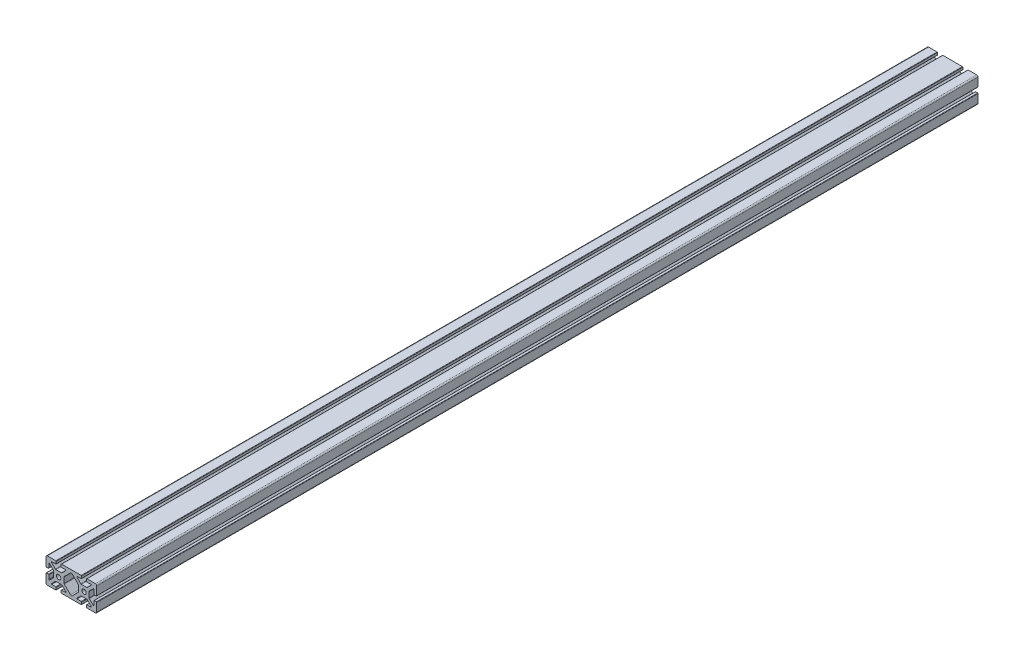
SolidWorks part; units mm, degrees
material "1060 Alloy"
ref_plane "Front Plane" through (0, 0, 0) normal (0, 0, 1) x (1, 0, 0)
ref_plane "Top Plane" through (0, 0, 0) normal (0, 1, 0) x (1, 0, 0)
ref_plane "Right Plane" through (0, 0, 0) normal (1, 0, 0) x (0, 0, -1)
sketch "Sketch1" plane through (0, 0, 0) normal (0, 0, 1) x (1, 0, 0)
  line L6 (11.2056, -5.1821) -> (1.4849, -14.9028)
  line L7 (-11.2056, -5.1821) -> (-1.4849, -14.9028)
  line L8 (-11.5571, 4.3336) -> (-11.5571, -4.3336)
  line L9 (-11.2056, 5.1821) -> (-1.4849, 14.9028)
  line L10 (11.2056, 5.1821) -> (1.4849, 14.9028)
  line L11 (11.5571, 4.3336) -> (11.5571, -4.3336)
  line L122 (-30.9, 15.5179) -> (-24.6, 15.5179)
  line L123 (-24, 16.1179) -> (-24, 19.4)
  line L124 (-24.6, 20) -> (-37.9, 20)
  line L125 (-40, 17.9) -> (-40, 4.6)
  line L126 (-39.4, 4) -> (-36.1179, 4)
  line L127 (-35.5179, 4.6) -> (-35.5179, 10.9)
  line L128 (-34.4936, 11.3243) -> (-28.3515, 5.1821)
  line L129 (-28, 4.3336) -> (-28, -4.3336)
  line L130 (-28.3515, -5.1821) -> (-34.4936, -11.3243)
  line L131 (-35.5179, -10.9) -> (-35.5179, -4.6)
  line L132 (-36.1179, -4) -> (-39.4, -4)
  line L133 (-40, -4.6) -> (-40, -17.9)
  line L134 (-37.9, -20) -> (-24.6, -20)
  line L135 (-24, -19.4) -> (-24, -16.1179)
  line L136 (-24.6, -15.5179) -> (-30.9, -15.5179)
  line L137 (-31.3243, -14.4936) -> (-25.1821, -8.3515)
  line L138 (-24.3336, -8) -> (-15.6664, -8)
  line L139 (-14.8179, -8.3515) -> (-8.6757, -14.4936)
  line L140 (-9.1, -15.5179) -> (-15.4, -15.5179)
  line L141 (-16, -16.1179) -> (-16, -19.4)
  line L142 (-15.4, -20) -> (15.4, -20)
  line L143 (16, -19.4) -> (16, -16.1179)
  line L144 (15.4, -15.5179) -> (9.1, -15.5179)
  line L145 (8.6757, -14.4936) -> (14.8179, -8.3515)
  line L146 (15.6664, -8) -> (24.3336, -8)
  line L147 (25.1821, -8.3515) -> (31.3243, -14.4936)
  line L148 (30.9, -15.5179) -> (24.6, -15.5179)
  line L149 (24, -16.1179) -> (24, -19.4)
  line L150 (24.6, -20) -> (37.9, -20)
  line L151 (40, -17.9) -> (40, -4.6)
  line L152 (39.4, -4) -> (36.1179, -4)
  line L153 (35.5179, -4.6) -> (35.5179, -10.9)
  line L154 (34.4936, -11.3243) -> (28.3515, -5.1821)
  line L155 (28, -4.3336) -> (28, 4.3336)
  line L156 (28.3515, 5.1821) -> (34.4936, 11.3243)
  line L157 (35.5179, 10.9) -> (35.5179, 4.6)
  line L158 (36.1179, 4) -> (39.4, 4)
  line L159 (40, 4.6) -> (40, 17.9)
  line L160 (37.9, 20) -> (24.6, 20)
  line L161 (24, 19.4) -> (24, 16.1179)
  line L162 (24.6, 15.5179) -> (30.9, 15.5179)
  line L163 (31.3243, 14.4936) -> (25.1821, 8.3515)
  line L164 (24.3336, 8) -> (15.6664, 8)
  line L165 (14.8179, 8.3515) -> (8.6757, 14.4936)
  line L166 (9.1, 15.5179) -> (15.4, 15.5179)
  line L167 (16, 16.1179) -> (16, 19.4)
  line L168 (15.4, 20) -> (-15.4, 20)
  line L169 (-16, 19.4) -> (-16, 16.1179)
  line L170 (-15.4, 15.5179) -> (-9.1, 15.5179)
  line L171 (-8.6757, 14.4936) -> (-14.8179, 8.3515)
  line L172 (-15.6664, 8) -> (-24.3336, 8)
  line L173 (-25.1821, 8.3515) -> (-31.3243, 14.4936)
  arc A8 (11.2056, -5.1821) -> (11.5571, -4.3336) centre (10.3571, -4.3336) ccw
  arc A9 (-1.4849, -14.9028) -> (1.4849, -14.9028) centre (0, -13.4179) ccw
  arc A10 (-11.5571, -4.3336) -> (-11.2056, -5.1821) centre (-10.3571, -4.3336) ccw
  arc A11 (-11.2056, 5.1821) -> (-11.5571, 4.3336) centre (-10.3571, 4.3336) ccw
  arc A12 (1.4849, 14.9028) -> (-1.4849, 14.9028) centre (0, 13.4179) ccw
  arc A13 (11.5571, 4.3336) -> (11.2056, 5.1821) centre (10.3571, 4.3336) ccw
  circle A14 centre (20, 0) radius 3.5
  circle A15 centre (-20, 0) radius 3.5
  arc A104 (-30.9, 15.5179) -> (-31.3243, 14.4936) centre (-30.9, 14.9179) ccw
  arc A105 (-24.6, 15.5179) -> (-24, 16.1179) centre (-24.6, 16.1179) ccw
  arc A106 (-24, 19.4) -> (-24.6, 20) centre (-24.6, 19.4) ccw
  arc A107 (-37.9, 20) -> (-40, 17.9) centre (-37.9, 17.9) ccw
  arc A108 (-40, 4.6) -> (-39.4, 4) centre (-39.4, 4.6) ccw
  arc A109 (-36.1179, 4) -> (-35.5179, 4.6) centre (-36.1179, 4.6) ccw
  arc A110 (-34.4936, 11.3243) -> (-35.5179, 10.9) centre (-34.9179, 10.9) ccw
  arc A111 (-28, 4.3336) -> (-28.3515, 5.1821) centre (-29.2, 4.3336) ccw
  arc A112 (-28.3515, -5.1821) -> (-28, -4.3336) centre (-29.2, -4.3336) ccw
  arc A113 (-35.5179, -10.9) -> (-34.4936, -11.3243) centre (-34.9179, -10.9) ccw
  arc A114 (-35.5179, -4.6) -> (-36.1179, -4) centre (-36.1179, -4.6) ccw
  arc A115 (-39.4, -4) -> (-40, -4.6) centre (-39.4, -4.6) ccw
  arc A116 (-40, -17.9) -> (-37.9, -20) centre (-37.9, -17.9) ccw
  arc A117 (-24.6, -20) -> (-24, -19.4) centre (-24.6, -19.4) ccw
  arc A118 (-24, -16.1179) -> (-24.6, -15.5179) centre (-24.6, -16.1179) ccw
  arc A119 (-31.3243, -14.4936) -> (-30.9, -15.5179) centre (-30.9, -14.9179) ccw
  arc A120 (-24.3336, -8) -> (-25.1821, -8.3515) centre (-24.3336, -9.2) ccw
  arc A121 (-14.8179, -8.3515) -> (-15.6664, -8) centre (-15.6664, -9.2) ccw
  arc A122 (-9.1, -15.5179) -> (-8.6757, -14.4936) centre (-9.1, -14.9179) ccw
  arc A123 (-15.4, -15.5179) -> (-16, -16.1179) centre (-15.4, -16.1179) ccw
  arc A124 (-16, -19.4) -> (-15.4, -20) centre (-15.4, -19.4) ccw
  arc A125 (15.4, -20) -> (16, -19.4) centre (15.4, -19.4) ccw
  arc A126 (16, -16.1179) -> (15.4, -15.5179) centre (15.4, -16.1179) ccw
  arc A127 (8.6757, -14.4936) -> (9.1, -15.5179) centre (9.1, -14.9179) ccw
  arc A128 (15.6664, -8) -> (14.8179, -8.3515) centre (15.6664, -9.2) ccw
  arc A129 (25.1821, -8.3515) -> (24.3336, -8) centre (24.3336, -9.2) ccw
  arc A130 (30.9, -15.5179) -> (31.3243, -14.4936) centre (30.9, -14.9179) ccw
  arc A131 (24.6, -15.5179) -> (24, -16.1179) centre (24.6, -16.1179) ccw
  arc A132 (24, -19.4) -> (24.6, -20) centre (24.6, -19.4) ccw
  arc A133 (37.9, -20) -> (40, -17.9) centre (37.9, -17.9) ccw
  arc A134 (40, -4.6) -> (39.4, -4) centre (39.4, -4.6) ccw
  arc A135 (36.1179, -4) -> (35.5179, -4.6) centre (36.1179, -4.6) ccw
  arc A136 (34.4936, -11.3243) -> (35.5179, -10.9) centre (34.9179, -10.9) ccw
  arc A137 (28, -4.3336) -> (28.3515, -5.1821) centre (29.2, -4.3336) ccw
  arc A138 (28.3515, 5.1821) -> (28, 4.3336) centre (29.2, 4.3336) ccw
  arc A139 (35.5179, 10.9) -> (34.4936, 11.3243) centre (34.9179, 10.9) ccw
  arc A140 (35.5179, 4.6) -> (36.1179, 4) centre (36.1179, 4.6) ccw
  arc A141 (39.4, 4) -> (40, 4.6) centre (39.4, 4.6) ccw
  arc A142 (40, 17.9) -> (37.9, 20) centre (37.9, 17.9) ccw
  arc A143 (24.6, 20) -> (24, 19.4) centre (24.6, 19.4) ccw
  arc A144 (24, 16.1179) -> (24.6, 15.5179) centre (24.6, 16.1179) ccw
  arc A145 (31.3243, 14.4936) -> (30.9, 15.5179) centre (30.9, 14.9179) ccw
  arc A146 (24.3336, 8) -> (25.1821, 8.3515) centre (24.3336, 9.2) ccw
  arc A147 (14.8179, 8.3515) -> (15.6664, 8) centre (15.6664, 9.2) ccw
  arc A148 (9.1, 15.5179) -> (8.6757, 14.4936) centre (9.1, 14.9179) ccw
  arc A149 (15.4, 15.5179) -> (16, 16.1179) centre (15.4, 16.1179) ccw
  arc A150 (16, 19.4) -> (15.4, 20) centre (15.4, 19.4) ccw
  arc A151 (-15.4, 20) -> (-16, 19.4) centre (-15.4, 19.4) ccw
  arc A152 (-16, 16.1179) -> (-15.4, 15.5179) centre (-15.4, 16.1179) ccw
  arc A153 (-8.6757, 14.4936) -> (-9.1, 15.5179) centre (-9.1, 14.9179) ccw
  arc A154 (-15.6664, 8) -> (-14.8179, 8.3515) centre (-15.6664, 9.2) ccw
  arc A155 (-25.1821, 8.3515) -> (-24.3336, 8) centre (-24.3336, 9.2) ccw
extrude "Boss-Extrude1" add sketch "Sketch1" along normal mid plane 1390.06
